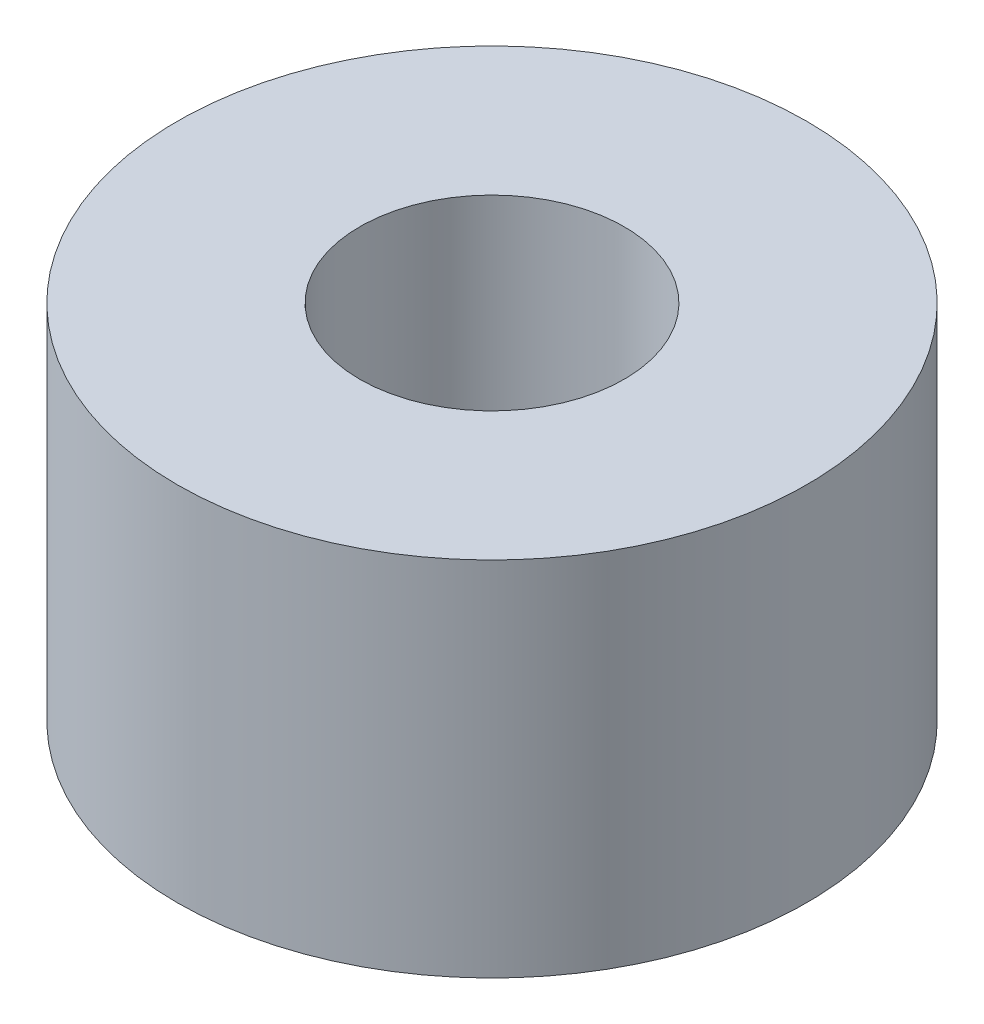
SolidWorks part; units mm, degrees
material "MC901"
ref_plane "正面" through (0, 0, 0) normal (0, 0, 1) x (1, 0, 0)
ref_plane "平面" through (0, 0, 0) normal (0, 1, 0) x (1, 0, 0)
ref_plane "右側面" through (0, 0, 0) normal (1, 0, 0) x (0, 0, -1)
sketch "ｽｹｯﾁ1" plane through (0, 0, 0) normal (0, 1, 0) x (1, 0, 0)
  circle A0 centre (0, 0) radius 5
  circle A1 centre (0, 0) radius 2.1
  dimension "D1" = 10
  dimension "D2" = 4.2
extrude "ﾎﾞｽ - 押し出し1" add sketch "ｽｹｯﾁ1" along normal blind 5.75
